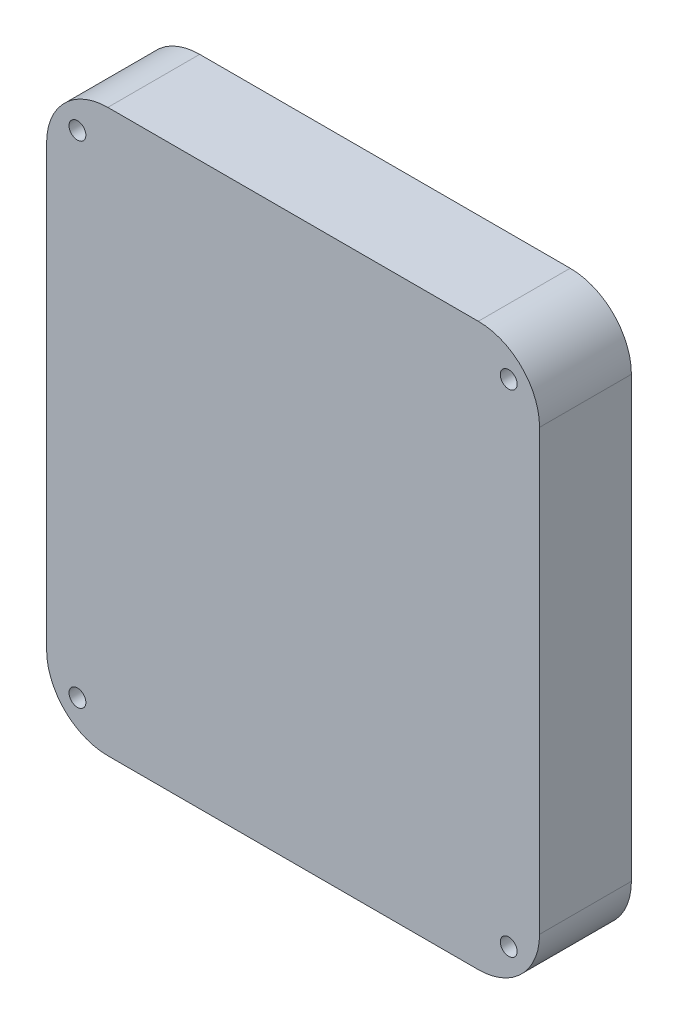
SolidWorks part; units mm, degrees
ref_plane "Ebene vorne" through (0, 0, 0) normal (0, 0, 1) x (1, 0, 0)
ref_plane "Ebene oben" through (0, 0, 0) normal (0, 1, 0) x (1, 0, 0)
ref_plane "Ebene rechts" through (0, 0, 0) normal (1, 0, 0) x (0, 0, -1)
sketch "Skizze1" plane through (0, 0, 0) normal (0, 0, 1) x (1, 0, 0)
  line L1 (-40.25, 45.85) -> (40.25, 45.85)
  line L2 (-40.25, 45.85) -> (-40.25, -45.85)
  line L3 (-40.25, -45.85) -> (40.25, -45.85)
  line L4 (40.25, 45.85) -> (40.25, -45.85)
  line L5 (-40.25, 45.85) -> (40.25, -45.85) construction
  line L6 (-40.25, -45.85) -> (40.25, 45.85) construction
  point P0 (0, 0)
  dimension "D1" = 80.5
  dimension "D2" = 91.7
extrude "Aufsatz-Linear austragen1" add sketch "Skizze1" along normal blind 15
fillet "Verrundung1" radius 10 4 edges at (-40.25, -45.85, 7.5) (40.25, -45.85, 7.5) (-40.25, 45.85, 7.5) (40.25, 45.85, 7.5)
sketch "Skizze2" plane through (0, 0, 15) normal (0, 0, 1) x (1, 0, 0)
  line L0 (30.25, 45.85) -> (-30.25, 45.85) construction
  line L1 (40.25, -45.85) -> (-40.25, -45.85) construction
  line L2 (40.25, -45.85) -> (40.25, 45.85) construction
  line L3 (40.25, 45.85) -> (-40.25, 45.85) construction
  line L4 (-40.25, -45.85) -> (-40.25, 45.85) construction
  line L5 (40.25, -45.85) -> (-40.25, 45.85) construction
  line L6 (40.25, 45.85) -> (-40.25, -45.85) construction
  line L7 (-40.25, 35.85) -> (-40.25, -35.85) construction
  line L8 (-35.2127, 40.1118) -> (35.2127, -40.1118) construction
  line L9 (-35.2127, -40.1118) -> (35.2127, 40.1118) construction
  circle A0 centre (-35.2127, 40.1118) radius 1.375
  circle A1 centre (35.2127, 40.1118) radius 1.375
  circle A2 centre (35.2127, -40.1118) radius 1.375
  circle A3 centre (-35.2127, -40.1118) radius 1.375
  point P8 (0, 0)
  point P18 (0, 0)
  dimension "D1" = 2.75
  dimension "D2" = 106.75
extrude "Schnitt-Linear austragen1" cut sketch "Skizze2" against normal through all
